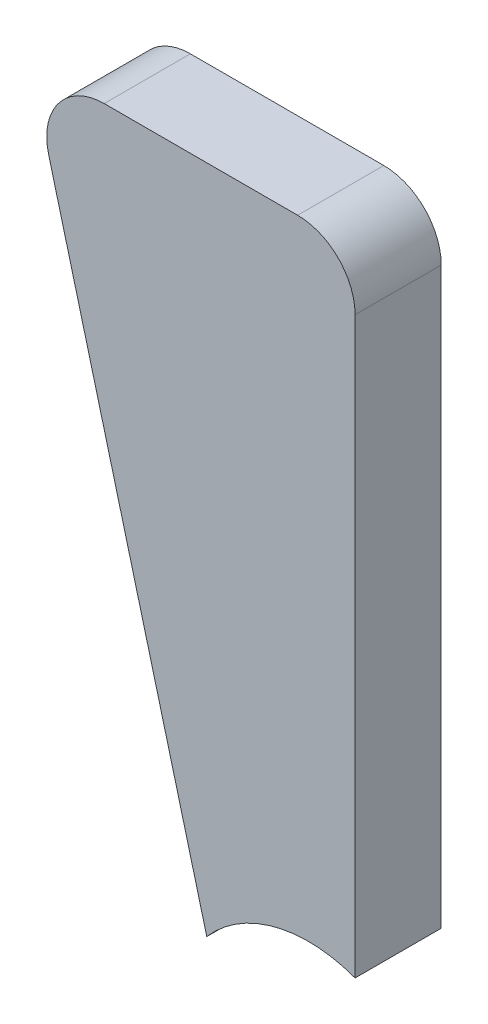
SolidWorks part; units mm, degrees
ref_plane "Plan de face" through (0, 0, 0) normal (0, 0, 1) x (1, 0, 0)
ref_plane "Plan de dessus" through (0, 0, 0) normal (0, 1, 0) x (1, 0, 0)
ref_plane "Plan de droite" through (0, 0, 0) normal (1, 0, 0) x (0, 0, -1)
sketch "Esquisse1" plane through (0, 0, 0) normal (0, 0, 1) x (1, 0, 0)
  line L0 (0, 0) -> (0, 33)
  line L1 (0, 33) -> (-17, 33)
  line L2 (-17, 33) -> (-7.746, -2)
  arc A0 (-7.746, -2) -> (0, 0) centre (-2.4368, -6.5621) cw
  point P6 (0, 0)
  dimension "D1" = 7
  dimension "D2" = 17
  dimension "D3" = 8
  dimension "D4" = 35
  dimension "D5" = 33
extrude "Boss.-Extru.1" add sketch "Esquisse1" along normal blind 4.5
fillet "Congé8" radius 3 1 edges at (-17, 33, 2.25)
fillet "Congé9" radius 3 1 edges at (0, 33, 2.25)
